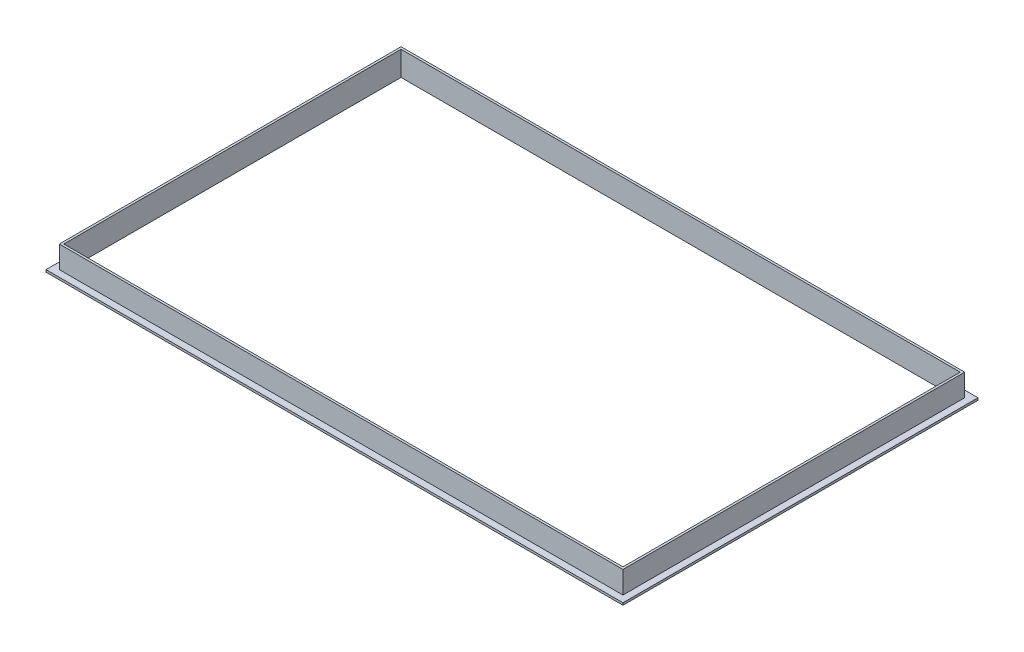
SolidWorks part; units mm, degrees
ref_plane "Ebene vorne" through (0, 0, 0) normal (0, 0, 1) x (1, 0, 0)
ref_plane "Ebene oben" through (0, 0, 0) normal (0, 1, 0) x (1, 0, 0)
ref_plane "Ebene rechts" through (0, 0, 0) normal (1, 0, 0) x (0, 0, -1)
sketch "Skizze1" plane through (0, 0, 0) normal (0, 1, 0) x (1, 0, 0)
  line L1 (0, 0) -> (520, 0)
  line L2 (0, 0) -> (0, 320)
  line L3 (0, 320) -> (520, 320)
  line L4 (520, 0) -> (520, 320)
  line L5 (8, 312) -> (512, 312)
  line L6 (8, 312) -> (8, 8)
  line L7 (8, 8) -> (512, 8)
  line L8 (512, 312) -> (512, 8)
  dimension "D1" = 520
  dimension "D2" = 320
  dimension "D3" = 8
  dimension "D4" = 504
  dimension "D5" = 304
  dimension "D6" = 8
extrude "Aufsatz-Linear austragen1" add sketch "Skizze1" along normal blind 2
sketch "Skizze2" plane through (0, 2, 0) normal (0, 1, 0) x (1, 0, 0)
  line L1 (8, 312) -> (512, 312)
  line L2 (8, 312) -> (8, 8)
  line L3 (8, 8) -> (512, 8)
  line L4 (512, 312) -> (512, 8)
  line L5 (6, 314) -> (514, 314)
  line L6 (6, 314) -> (6, 6)
  line L7 (6, 6) -> (514, 6)
  line L8 (514, 314) -> (514, 6)
  dimension "D1" = 2
  dimension "D2" = 2
  dimension "D3" = 2
  dimension "D4" = 2
extrude "Aufsatz-Linear austragen2" add sketch "Skizze2" along normal blind 20
